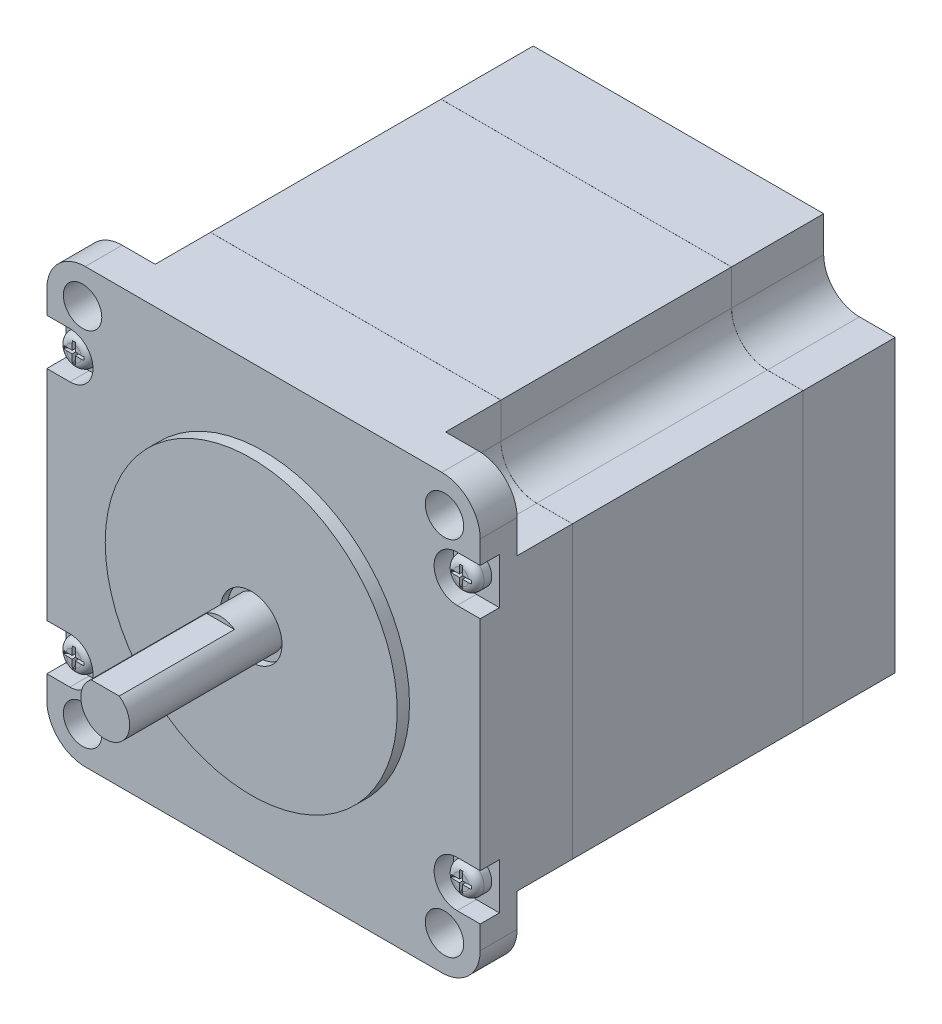
SolidWorks part; units mm, degrees
material "1060 Alloy"
ref_plane "Front Plane" through (0, 0, 0) normal (0, 0, 1) x (1, 0, 0)
ref_plane "Top Plane" through (0, 0, 0) normal (0, 1, 0) x (1, 0, 0)
ref_plane "Right Plane" through (0, 0, 0) normal (1, 0, 0) x (0, 0, -1)
sketch "Sketch1" plane through (0, 0, 0) normal (0, 0, 1) x (1, 0, 0)
  line L1 (-28.2, -28.2) -> (28.2, -28.2)
  line L2 (-28.2, -28.2) -> (-28.2, 28.2)
  line L3 (-28.2, 28.2) -> (28.2, 28.2)
  line L4 (28.2, -28.2) -> (28.2, 28.2)
  line L5 (-28.2, -28.2) -> (28.2, 28.2) construction
  line L6 (-28.2, 28.2) -> (28.2, -28.2) construction
  point P0 (0, 0)
  dimension "D1" = 56.4
  dimension "D2" = 56.4
extrude "Boss-Extrude1" add sketch "Sketch1" against normal blind 54
sketch "Sketch2" plane through (0, 0, 0) normal (0, 0, 1) x (1, 0, 0)
  circle A0 centre (0, 0) radius 19
  dimension "D1" = 38
extrude "Boss-Extrude2" add sketch "Sketch2" along normal blind 1.6
sketch "Sketch3" plane through (0, 0, 0) normal (0, 0, 1) x (1, 0, 0)
  line L0 (-23.55, 23.55) -> (23.55, 23.55) construction
  line L1 (23.55, 23.55) -> (23.55, -23.55) construction
  line L2 (23.55, -23.55) -> (-23.55, -23.55) construction
  line L3 (-23.55, -23.55) -> (-23.55, 23.55) construction
  line L4 (23.55, 23.55) -> (-23.55, -23.55) construction
  circle A0 centre (-23.55, 23.55) radius 2.5
  circle A1 centre (23.55, 23.55) radius 2.5
  circle A2 centre (23.55, -23.55) radius 2.5
  circle A3 centre (-23.55, -23.55) radius 2.5
  dimension "D1" = 5
  dimension "D2" = 47.1
  dimension "D3" = 47.1
extrude "Cut-Extrude1" cut sketch "Sketch3" against normal blind 10
sketch "Sketch6" plane through (0, 0, -54) normal (0, 0, -1) x (-1, 0, 0)
  line L0 (-18.9, 23.55) -> (-18.9, 28.2)
  line L1 (-28.2, 28.2) -> (28.2, 28.2) construction
  line L2 (-23.55, 18.9) -> (-28.2, 18.9)
  line L3 (-28.2, -28.2) -> (-28.2, 28.2) construction
  line L4 (-28.2, 0) -> (28.2, 0) construction
  line L5 (28.2, 28.2) -> (28.2, -28.2) construction
  line L6 (0, 28.2) -> (0, -28.2) construction
  line L7 (28.2, -28.2) -> (-28.2, -28.2) construction
  line L8 (-18.9, 28.2) -> (-28.2, 28.2)
  line L9 (-28.2, 28.2) -> (-28.2, 18.9)
  line L10 (28.2, 28.2) -> (28.2, 18.9)
  line L11 (18.9, 28.2) -> (28.2, 28.2)
  line L12 (23.55, 18.9) -> (28.2, 18.9)
  line L13 (18.9, 23.55) -> (18.9, 28.2)
  line L14 (-28.2, -28.2) -> (-28.2, -18.9)
  line L15 (-18.9, -28.2) -> (-28.2, -28.2)
  line L16 (-23.55, -18.9) -> (-28.2, -18.9)
  line L17 (-18.9, -23.55) -> (-18.9, -28.2)
  line L18 (18.9, -23.55) -> (18.9, -28.2)
  line L19 (23.55, -18.9) -> (28.2, -18.9)
  line L20 (18.9, -28.2) -> (28.2, -28.2)
  line L21 (28.2, -28.2) -> (28.2, -18.9)
  arc A4 (23.55, 18.9) -> (18.9, 23.55) centre (23.55, 23.55) cw
  arc A5 (-23.55, -18.9) -> (-18.9, -23.55) centre (-23.55, -23.55) cw
  arc A6 (-23.55, 18.9) -> (-18.9, 23.55) centre (-23.55, 23.55) ccw
  arc A7 (23.55, -18.9) -> (18.9, -23.55) centre (23.55, -23.55) ccw
extrude "Cut-Extrude2" cut sketch "Sketch6" against normal blind 49.2
fillet "Fillet1" radius 5 4 edges at (28.2, -28.2, -2.4) (-28.2, -28.2, -2.4) (-28.2, 28.2, -2.4) (28.2, 28.2, -2.4)
sketch "Sketch7" plane through (-28.2, 0, 0) normal (-1, 0, 0) x (0, 0, 1)
  line L0 (-4.8, 28.2) -> (-54, 28.2) construction
  line L1 (-12, -28.2) -> (-42, -28.2)
  line L2 (-12, -28.2) -> (-12, 28.2)
  line L3 (-12, 28.2) -> (-42, 28.2)
  line L4 (-42, -28.2) -> (-42, 28.2)
  line L5 (-12, -28.2) -> (-42, 28.2) construction
  line L6 (-12, 28.2) -> (-42, -28.2) construction
  line L7 (-27, -28.2) -> (-27, 28.2) construction
  line L9 (-54, 0) -> (0, 0) construction
  line L10 (-54, 18.9) -> (-54, -18.9) construction
  line L11 (-42.01, -28.21) -> (-42.01, 28.21)
  line L12 (-11.99, 28.21) -> (-42.01, 28.21)
  line L13 (-11.99, -28.21) -> (-11.99, 28.21)
  line L14 (-11.99, -28.21) -> (-42.01, -28.21)
  point P0 (-27, 0)
  dimension "D1" = 30
  dimension "D2" = 0.01
extrude "Cut-Extrude3" cut sketch "Sketch7" against normal through all
sketch "Sketch8" plane through (0, 0, -54) normal (0, 0, -1) x (-1, 0, 0)
  circle A0 centre (0, 0) radius 6
  dimension "D1" = 12
extrude "Cut-Extrude4" cut sketch "Sketch8" against normal blind 3
sketch "Sketch9" plane through (0, 0, -51) normal (0, 0, -1) x (-1, 0, 0)
  circle A0 centre (0, 0) radius 3
  dimension "D1" = 6
extrude "Boss-Extrude3" add sketch "Sketch9" along normal blind 1.5 separate body
chamfer "Chamfer1" distance 0.5 angle 45 1 edges at (-3, 0, -52.5)
sketch "Sketch10" plane through (0, 0, 1.6) normal (0, 0, 1) x (1, 0, 0)
  circle A0 centre (0, 0) radius 4
  dimension "D1" = 8
extrude "Cut-Extrude5" cut sketch "Sketch10" against normal blind 1
sketch "Sketch11" plane through (0, 0, 0.6) normal (0, 0, 1) x (1, 0, 0)
  circle A0 centre (0, 0) radius 3.175
  dimension "D1" = 6.35
extrude "Boss-Extrude4" add sketch "Sketch11" along normal blind 20 separate body
sketch "Sketch12" plane through (0, 0, 20.6) normal (0, 0, 1) x (1, 0, 0)
  line L0 (-1.8223, 2.6) -> (1.8223, 2.6)
  arc A0 (1.8223, 2.6) -> (-1.8223, 2.6) centre (0, 0) ccw
  dimension "D1" = 2.6
extrude "Cut-Extrude6" cut sketch "Sketch12" against normal blind 15
sketch "Sketch13" plane through (0, 0, 0) normal (0, 0, 1) x (1, 0, 0)
  line L0 (-28.2, 23.2) -> (-28.2, -23.2) construction
  line L1 (23.2, 28.2) -> (-23.2, 28.2) construction
  line L2 (-25.2, 20.2) -> (-28.2, 20.2)
  line L3 (-28.2, 20.2) -> (-28.2, 14.2)
  line L4 (-28.2, 14.2) -> (-25.2, 14.2)
  line L5 (0, 28.2) -> (0, 21.4759) construction
  line L6 (-28.2, 0) -> (-22.9335, 0) construction
  line L7 (28.2, 14.2) -> (25.2, 14.2)
  line L8 (28.2, 20.2) -> (28.2, 14.2)
  line L9 (25.2, 20.2) -> (28.2, 20.2)
  line L10 (25.2, -20.2) -> (28.2, -20.2)
  line L11 (28.2, -20.2) -> (28.2, -14.2)
  line L12 (28.2, -14.2) -> (25.2, -14.2)
  line L13 (-28.2, -14.2) -> (-25.2, -14.2)
  line L14 (-28.2, -20.2) -> (-28.2, -14.2)
  line L15 (-25.2, -20.2) -> (-28.2, -20.2)
  arc A0 (-25.2, 14.2) -> (-25.2, 20.2) centre (-25.2, 17.2) ccw
  arc A1 (25.2, 14.2) -> (25.2, 20.2) centre (25.2, 17.2) cw
  arc A2 (25.2, -14.2) -> (25.2, -20.2) centre (25.2, -17.2) ccw
  arc A3 (-25.2, -14.2) -> (-25.2, -20.2) centre (-25.2, -17.2) cw
  dimension "D1" = 6
  dimension "D2" = 3
  dimension "D3" = 11
extrude "Cut-Extrude7" cut sketch "Sketch13" against normal blind 2.5
sketch "Sketch14" plane through (0, 0, -2.5) normal (0, 0, 1) x (1, 0, 0)
  circle A0 centre (-25.2, 17.2) radius 2
  circle A1 centre (25.2, 17.2) radius 2
  circle A2 centre (25.2, -17.2) radius 2
  circle A3 centre (-25.2, -17.2) radius 2
  dimension "D1" = 4
extrude "Boss-Extrude5" add sketch "Sketch14" along normal blind 2 separate body
fillet "Fillet2" radius 1 1 edges at (-23.2, 17.2, -0.5)
fillet "Fillet3" radius 1 1 edges at (-23.2, -17.2, -0.5)
fillet "Fillet4" radius 1 1 edges at (27.2, -17.2, -0.5)
fillet "Fillet5" radius 1 1 edges at (27.2, 17.2, -0.5)
sketch "Sketch15" plane through (0, 0, -0.5) normal (0, 0, 1) x (1, 0, 0)
  line L0 (-25.399, 17.4039) -> (-25.399, 18.476)
  line L1 (-25.399, 15.924) -> (-25.001, 15.924)
  line L2 (-25.399, 15.924) -> (-25.399, 16.9961)
  line L3 (-25.399, 18.476) -> (-25.001, 18.476)
  line L4 (-25.001, 15.924) -> (-25.001, 16.9961)
  line L5 (-25.399, 15.924) -> (-25.001, 18.476) construction
  line L6 (-25.399, 18.476) -> (-25.001, 15.924) construction
  line L7 (-26.5074, 16.9961) -> (-25.399, 16.9961)
  line L8 (-26.5074, 16.9961) -> (-26.5074, 17.4039)
  line L9 (-26.5074, 17.4039) -> (-25.399, 17.4039)
  line L10 (-23.8926, 16.9961) -> (-23.8926, 17.4039)
  line L11 (-26.5074, 16.9961) -> (-23.8926, 17.4039) construction
  line L12 (-26.5074, 17.4039) -> (-23.8926, 16.9961) construction
  line L13 (-25.001, 16.9961) -> (-23.8926, 16.9961)
  line L14 (-25.001, 17.4039) -> (-23.8926, 17.4039)
  line L15 (-25.001, 17.4039) -> (-25.001, 18.476)
  line L16 (0, 28.2) -> (0, 21.2733) construction
  line L17 (23.2, 28.2) -> (-23.2, 28.2) construction
  line L18 (-28.2, 0) -> (-21.4297, 0) construction
  line L19 (-28.2, 14.2) -> (-28.2, -14.2) construction
  line L20 (26.5074, 17.4039) -> (23.8926, 16.9961) construction
  line L21 (26.5074, 16.9961) -> (23.8926, 17.4039) construction
  line L22 (25.399, 18.476) -> (25.001, 15.924) construction
  line L23 (25.399, 15.924) -> (25.001, 18.476) construction
  line L24 (25.001, 17.4039) -> (25.001, 18.476)
  line L25 (25.001, 17.4039) -> (23.8926, 17.4039)
  line L26 (25.001, 16.9961) -> (23.8926, 16.9961)
  line L27 (23.8926, 16.9961) -> (23.8926, 17.4039)
  line L28 (26.5074, 17.4039) -> (25.399, 17.4039)
  line L29 (26.5074, 16.9961) -> (26.5074, 17.4039)
  line L30 (26.5074, 16.9961) -> (25.399, 16.9961)
  line L31 (25.001, 15.924) -> (25.001, 16.9961)
  line L32 (25.399, 18.476) -> (25.001, 18.476)
  line L33 (25.399, 15.924) -> (25.399, 16.9961)
  line L34 (25.399, 15.924) -> (25.001, 15.924)
  line L35 (25.399, 17.4039) -> (25.399, 18.476)
  line L36 (25.399, -15.924) -> (25.001, -18.476) construction
  line L37 (25.399, -18.476) -> (25.001, -15.924) construction
  line L38 (26.5074, -16.9961) -> (23.8926, -17.4039) construction
  line L39 (26.5074, -17.4039) -> (23.8926, -16.9961) construction
  line L40 (25.399, -17.4039) -> (25.399, -18.476)
  line L41 (25.399, -15.924) -> (25.001, -15.924)
  line L42 (25.399, -15.924) -> (25.399, -16.9961)
  line L43 (25.399, -18.476) -> (25.001, -18.476)
  line L44 (25.001, -15.924) -> (25.001, -16.9961)
  line L45 (26.5074, -16.9961) -> (25.399, -16.9961)
  line L46 (26.5074, -16.9961) -> (26.5074, -17.4039)
  line L47 (26.5074, -17.4039) -> (25.399, -17.4039)
  line L48 (23.8926, -16.9961) -> (23.8926, -17.4039)
  line L49 (25.001, -16.9961) -> (23.8926, -16.9961)
  line L50 (25.001, -17.4039) -> (23.8926, -17.4039)
  line L51 (25.001, -17.4039) -> (25.001, -18.476)
  line L52 (-26.5074, -17.4039) -> (-23.8926, -16.9961) construction
  line L53 (-26.5074, -16.9961) -> (-23.8926, -17.4039) construction
  line L54 (-25.399, -18.476) -> (-25.001, -15.924) construction
  line L55 (-25.399, -15.924) -> (-25.001, -18.476) construction
  line L56 (-25.001, -17.4039) -> (-25.001, -18.476)
  line L57 (-25.001, -17.4039) -> (-23.8926, -17.4039)
  line L58 (-25.001, -16.9961) -> (-23.8926, -16.9961)
  line L59 (-23.8926, -16.9961) -> (-23.8926, -17.4039)
  line L60 (-26.5074, -17.4039) -> (-25.399, -17.4039)
  line L61 (-26.5074, -16.9961) -> (-26.5074, -17.4039)
  line L62 (-26.5074, -16.9961) -> (-25.399, -16.9961)
  line L63 (-25.001, -15.924) -> (-25.001, -16.9961)
  line L64 (-25.399, -18.476) -> (-25.001, -18.476)
  line L65 (-25.399, -15.924) -> (-25.399, -16.9961)
  line L66 (-25.399, -15.924) -> (-25.001, -15.924)
  line L67 (-25.399, -17.4039) -> (-25.399, -18.476)
  point P0 (-25.2, 17.2)
  point P6 (-25.2, 17.2)
  point P36 (25.2, 17.2)
  point P49 (25.2, -17.2)
  point P62 (-25.2, -17.2)
extrude "Cut-Extrude8" cut sketch "Sketch15" against normal blind 1.2
chamfer "Chamfer2" distance 1 angle 45 4 edges at (-25.2, 15.924, -1.7) (-23.8926, 17.2, -1.7) (-26.5074, 17.2, -1.7) (-25.2, 18.476, -1.7)
chamfer "Chamfer3" distance 1 angle 45 4 edges at (26.5074, 17.2, -1.7) (25.2, 18.476, -1.7) (25.2, 15.924, -1.7) (23.8926, 17.2, -1.7)
chamfer "Chamfer4" distance 1 angle 45 4 edges at (25.2, -15.924, -1.7) (25.2, -18.476, -1.7) (23.8926, -17.2, -1.7) (26.5074, -17.2, -1.7)
chamfer "Chamfer5" distance 1 angle 45 4 edges at (-23.8926, -17.2, -1.7) (-26.5074, -17.2, -1.7) (-25.2, -18.476, -1.7) (-25.2, -15.924, -1.7)
